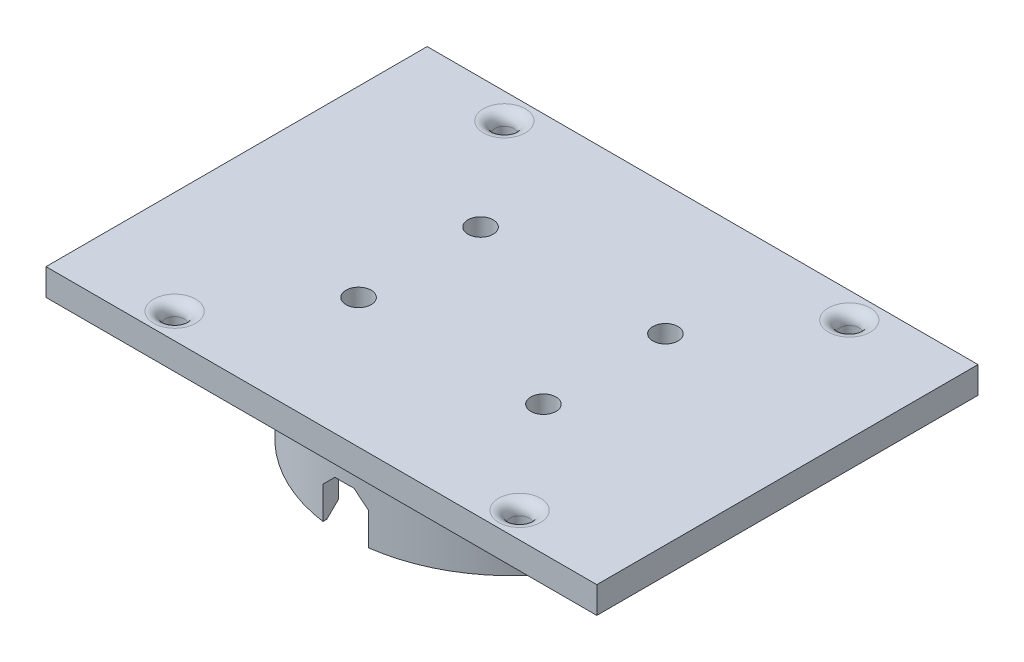
SolidWorks part; units mm, degrees
material "PLA"
ref_plane "Front Plane" through (0, 0, 0) normal (0, 0, 1) x (1, 0, 0)
ref_plane "Top Plane" through (0, 0, 0) normal (0, 1, 0) x (1, 0, 0)
ref_plane "Right Plane" through (0, 0, 0) normal (1, 0, 0) x (0, 0, -1)
sketch "Sketch1" plane through (0, 0, 0) normal (0, 1, 0) x (1, 0, 0)
  line L1 (-36.125, -25) -> (36.125, -25)
  line L2 (-36.125, -25) -> (-36.125, 25)
  line L3 (-36.125, 25) -> (36.125, 25)
  line L4 (36.125, -25) -> (36.125, 25)
  line L5 (-36.125, -25) -> (36.125, 25) construction
  line L6 (-36.125, 25) -> (36.125, -25) construction
  point P0 (0, 0)
  dimension "D1" = 50
  dimension "D2" = 72.25
extrude "Boss-Extrude1" add sketch "Sketch1" along normal mid plane 4
sketch "Sketch2" plane through (0, 2, 0) normal (0, 1, 0) x (1, 0, 0)
  line L0 (0, -1000) -> (0, 49000) construction
  line L1 (36.125, -25) -> (36.125, 25) construction
  circle A0 centre (12.125, -8) radius 1.65
  circle A1 centre (12.125, 8) radius 1.65
  circle A2 centre (-12.125, -8) radius 1.65
  circle A3 centre (-12.125, 8) radius 1.65
  dimension "D1" = 3.3
  dimension "D2" = 3.3
  dimension "D3" = 24
  dimension "D4" = 24
  dimension "D5" = 8
  dimension "D6" = 8
extrude "Cut-Extrude1" cut sketch "Sketch2" against normal blind 10
sketch "Sketch3" plane through (0, -2, 0) normal (0, -1, 0) x (1, 0, 0)
  circle A0 centre (0, 0) radius 22
  circle A1 centre (0, 0) radius 20
  dimension "D1" = 44
  dimension "D2" = 2
extrude "Boss-Extrude2" add sketch "Sketch3" along normal blind 10
chamfer "Chamfer2" distance 1.5 angle 45 1 edges at (0, -12, -20)
sketch "Sketch6" plane through (0, 0, 0) normal (1, 0, 0) x (0, 0, -1)
  line L0 (-22, -12) -> (22, -12) construction
  line L1 (-4.5, -12) -> (4.5, -12)
  line L2 (-4.5, -12) -> (-4.5, -2)
  line L3 (-4.5, -2) -> (4.5, -2)
  line L4 (4.5, -12) -> (4.5, -2)
  line L5 (-22, -2) -> (22, -2) construction
  point P6 (0, -2)
  dimension "D1" = 9
extrude "Cut-Extrude3" cut sketch "Sketch6" against normal through all both and the other way through all
sketch "Sketch4" plane through (0, -2, 0) normal (0, -1, 0) x (1, 0, 0)
  line L0 (-1000, 0) -> (49000, 0) construction
  line L2 (-6, -3) -> (-3, -3)
  line L3 (-6, -3) -> (-6, 3)
  line L4 (-6, 3) -> (-3, 3)
  line L5 (-3, -3) -> (-3, 3)
  line L6 (-6, -3) -> (-3, 3) construction
  line L7 (-6, 3) -> (-3, -3) construction
  line L8 (3, -3) -> (6, -3)
  line L9 (3, -3) -> (3, 3)
  line L10 (3, 3) -> (6, 3)
  line L11 (6, -3) -> (6, 3)
  line L12 (3, -3) -> (6, 3) construction
  line L13 (3, 3) -> (6, -3) construction
  point P1 (-4.5, 0)
  point P8 (4.5, 0)
  dimension "D1" = 3
  dimension "D2" = 3
  dimension "D3" = 6
  dimension "D4" = 3
extrude "Boss-Extrude3" add sketch "Sketch4" along normal blind 6
fillet "Fillet1" radius 0.5 8 edges at (6, -2, 0) (-6, -2, 0) (3, -2, 0) (-3, -2, 0) (-4.5, -2, 3) (4.5, -2, 3) (4.5, -2, -3) (-4.5, -2, -3)
sketch "Sketch5" plane through (-6, 0, 0) normal (-1, 0, 0) x (0, 0, 1)
  line L0 (-3, -2.5) -> (3, -8) construction
  line L1 (3, -2.5) -> (-3, -8) construction
  circle A0 centre (0, -5.25) radius 1.75
  point P8 (0, -5.25)
  dimension "D1" = 3.5
extrude "Cut-Extrude2" cut sketch "Sketch5" against normal up to surface (12 mm away) up to face at (6, -5.25, 0)
chamfer "Chamfer3" distance 1.5 angle 45 4 edges at (4.5, -8, -3) (4.5, -8, 3) (-4.5, -8, 3) (-4.5, -8, -3)
sketch "Sketch7" plane through (0, 2, 0) normal (0, 1, 0) x (1, 0, 0)
  line L0 (-22.625, -997.4472) -> (-22.625, 49002.5528) construction
  line L1 (-36.125, 25) -> (-36.125, -25) construction
  line L2 (36.125, 25) -> (-36.125, 25) construction
  line L3 (0, -1000) -> (0, 49000) construction
  circle A0 centre (-22.625, 21.625) radius 1.25
  circle A1 centre (-22.625, -21.625) radius 1.25
  circle A2 centre (22.625, -21.625) radius 1.25
  circle A3 centre (22.625, 21.625) radius 1.25
  dimension "D2" = 2.5
  dimension "D3" = 2.5
  dimension "D1" = 13.5
  dimension "D4" = 43.25
  dimension "D5" = 3.375
extrude "Cut-Extrude4" cut sketch "Sketch7" against normal blind 10
fillet "Fillet2" radius 1.5 8 edges at (22.625, 2, 20.375) (22.625, -2, 20.375) (22.625, 2, -22.875) (22.625, -2, -22.875) (-22.625, 2, -20.375) (-22.625, -2, -22.875) (-22.625, 2, 22.875) (-22.625, -2, 20.375)
sketch "Sketch8" plane through (0, 0, 0) normal (0, 0, 1) x (1, 0, 0)
  line L0 (0, -1000) -> (0, 49000) construction
  line L1 (-21.5349, -12) -> (21.5349, -12) construction
  line L2 (-3, -12) -> (3, -12)
  line L3 (-3, -12) -> (-3, -6)
  line L4 (-3, -6) -> (3, -6)
  line L5 (3, -12) -> (3, -6)
  line L6 (-3, -12) -> (3, -6) construction
  line L7 (-3, -6) -> (3, -12) construction
  line L8 (-3, -9.75) -> (-3, -14.25) construction
  point P1 (0, -9)
extrude "Cut-Extrude5" cut sketch "Sketch8" against normal through all both and the other way through all
chamfer "Chamfer4" distance 1.75 angle 45 8 edges at (-20.511, -2, -4.5) (20.511, -2, -4.5) (20.511, -2, 4.5) (-20.511, -2, 4.5) (-3, -6, 20.7841) (-3, -6, -20.7841) (3, -6, 20.7841) (3, -6, -20.7841)
chamfer "Chamfer5" distance 0.5 angle 45 4 edges at (36.125, -2, 0) (0, -2, -25) (-36.125, -2, 0) (0, -2, 25)
